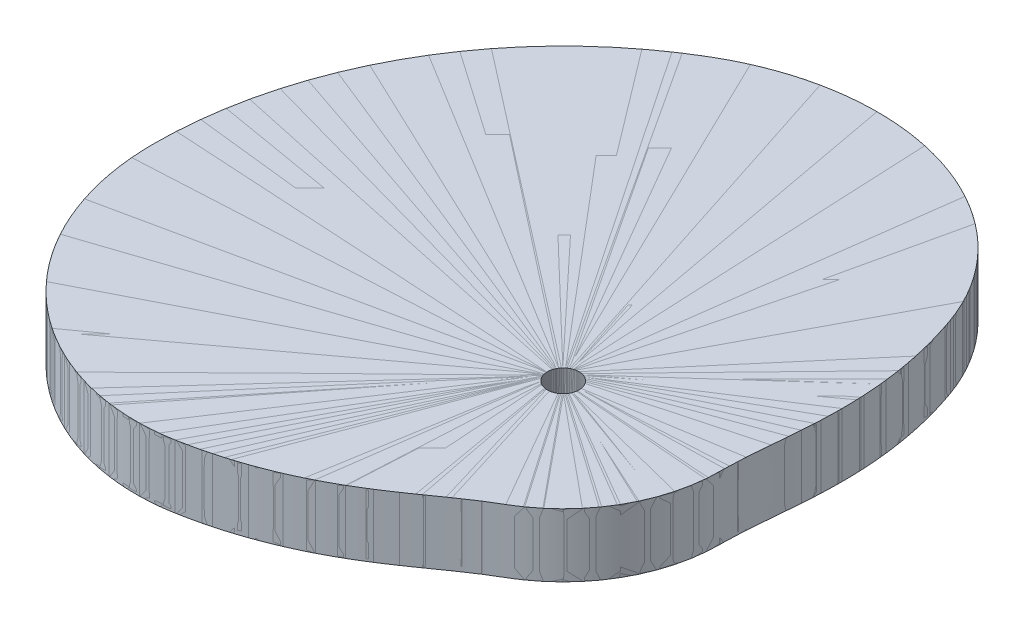
SolidWorks part; units mm, degrees
ref_plane "前视基准面" through (0, 0, 0) normal (0, 0, 1) x (1, 0, 0)
ref_plane "上视基准面" through (0, 0, 0) normal (0, 1, 0) x (1, 0, 0)
ref_plane "右视基准面" through (0, 0, 0) normal (1, 0, 0) x (0, 0, -1)
other "Configuration Table"
sketch "草图1" plane through (0, 0, 0) normal (0, 0, 1) x (1, 0, 0)
  line L0 (0, -20200) -> (0, 200) construction
  line L1 (5, 0) -> (130, 0)
  line L2 (130, 0) -> (130, -20)
  line L3 (130, -20) -> (5, -20)
  line L4 (5, -20) -> (5, 0)
revolve "旋转1" add sketch "草图1" angle 360 about L0
sketch "草图2" plane through (0, 0, 0) normal (0, 1, 0) x (1, 0, 0)
  line L0 (0, 0) -> (50, 0) construction
  arc A0 (49.5, 0) -> (49.5868, 4.4012) centre (162.6884, -0.0309) cw
  arc A1 (49.5868, 4.4012) -> (49.8358, 8.9099) centre (194.8962, -1.3625) cw
  arc A2 (49.8358, 8.9099) -> (50.213, 13.6312) centre (319.2819, -10.2396) cw
  arc A3 (50.213, 13.6312) -> (50.663, 18.6649) centre (3915.5987, -329.3799) cw
  arc A4 (50.663, 18.6649) -> (51.1105, 24.1021) centre (-309.0879, 51.0135) ccw
  arc A5 (51.1105, 24.1021) -> (51.462, 30.0213) centre (-145.0959, 38.7218) ccw
  arc A6 (51.462, 30.0213) -> (51.6071, 36.4857) centre (-98.2755, 36.6179) ccw
  arc A7 (51.6071, 36.4857) -> (51.4215, 43.5396) centre (-79.0428, 36.5763) ccw
  arc A8 (51.4215, 43.5396) -> (50.7686, 51.2069) centre (-70.6967, 37.0025) ccw
  arc A9 (50.7686, 51.2069) -> (49.5032, 59.4882) centre (-67.8394, 37.3214) ccw
  arc A10 (49.5032, 59.4882) -> (47.4745, 68.3602) centre (-68.1876, 37.2436) ccw
  arc A11 (47.4745, 68.3602) -> (44.5307, 77.769) centre (-70.5306, 36.6049) ccw
  arc A12 (44.5307, 77.769) -> (40.298, 87.1155) centre (-14.8762, 56.4971) ccw
  arc A13 (40.298, 87.1155) -> (34.5682, 95.7489) centre (-16.8999, 55.3723) ccw
  arc A14 (34.5682, 95.7489) -> (27.4814, 103.4715) centre (-18.8355, 53.855) ccw
  arc A15 (27.4814, 103.4715) -> (19.2044, 110.1045) centre (-20.5276, 52.0448) ccw
  arc A16 (19.2044, 110.1045) -> (9.925, 115.4961) centre (-21.8914, 50.0559) ccw
  arc A17 (9.925, 115.4961) -> (-0.1518, 119.5233) centre (-22.8862, 48.016) ccw
  arc A18 (-0.1518, 119.5233) -> (-10.8076, 122.0939) centre (-23.5139, 46.0515) ccw
  arc A19 (-10.8076, 122.0939) -> (-21.8153, 123.1479) centre (-23.8137, 44.2768) ccw
  arc A20 (-21.8153, 123.1479) -> (-32.943, 122.6584) centre (-23.8548, 42.7851) ccw
  arc A21 (-32.943, 122.6584) -> (-43.9585, 120.6313) centre (-23.7281, 41.6427) ccw
  arc A22 (-43.9585, 120.6313) -> (-54.634, 117.105) centre (-23.5377, 40.8858) ccw
  arc A23 (-54.634, 117.105) -> (-64.75, 112.1503) centre (-23.3663, 40.4621) ccw
  arc A24 (-64.75, 112.1503) -> (-129.5, 0) centre (0, 0) ccw
  arc A25 (-129.5, 0) -> (-128.7329, -11.2381) centre (-46.7244, 0.0047) ccw
  arc A26 (-128.7329, -11.2381) -> (-126.449, -22.2464) centre (-47.177, -0.0586) ccw
  arc A27 (-126.449, -22.2464) -> (-122.6968, -32.7998) centre (-47.9277, -0.2722) ccw
  arc A28 (-122.6968, -32.7998) -> (-117.5569, -42.6814) centre (-48.9804, -0.7337) ccw
  arc A29 (-117.5569, -42.6814) -> (-111.1402, -51.6872) centre (-50.2517, -1.5152) ccw
  arc A30 (-111.1402, -51.6872) -> (-103.5861, -59.6302) centre (-51.6388, -2.6621) ccw
  arc A31 (-103.5861, -59.6302) -> (-95.0601, -66.3433) centre (-53.0262, -4.1879) ccw
  arc A32 (-95.0601, -66.3433) -> (-85.7511, -71.6838) centre (-54.2954, -6.0694) ccw
  arc A33 (-85.7511, -71.6838) -> (-75.8682, -75.5353) centre (-55.3359, -8.2449) ccw
  arc A34 (-75.8682, -75.5353) -> (-65.6369, -77.8113) centre (-56.0575, -10.6155) ccw
  arc A35 (-65.6369, -77.8113) -> (-55.2952, -78.4568) centre (-56.4038, -13.0504) ccw
  arc A36 (-55.2952, -78.4568) -> (-45.0846, -77.4492) centre (-56.366, -15.3653) ccw
  arc A37 (-45.0846, -77.4492) -> (-35.4644, -75.2942) centre (-66.9661, 42.7788) ccw
  arc A38 (-35.4644, -75.2942) -> (-26.7667, -72.6152) centre (-66.3477, 40.4304) ccw
  arc A39 (-26.7667, -72.6152) -> (-18.9621, -69.5703) centre (-66.241, 40.09) ccw
  arc A40 (-18.9621, -69.5703) -> (-11.9957, -66.3021) centre (-67.3934, 42.7239) ccw
  arc A41 (-11.9957, -66.3021) -> (-5.794, -62.9359) centre (-71.1974, 50.1649) ccw
  arc A42 (-5.794, -62.9359) -> (-0.2683, -59.578) centre (-80.8498, 66.8001) ccw
  arc A43 (-0.2683, -59.578) -> (4.6822, -56.314) centre (-106.082, 106.2959) ccw
  arc A44 (4.6822, -56.314) -> (9.1672, -53.2079) centre (-198.7229, 242.1712) ccw
  arc A45 (9.1672, -53.2079) -> (13.3016, -50.3013) centre (2243.0507, -3226.318) cw
  arc A46 (13.3016, -50.3013) -> (17.2017, -47.614) centre (168.5087, -271.3864) cw
  arc A47 (17.2017, -47.614) -> (20.9819, -45.144) centre (98.6281, -168.1038) cw
  arc A48 (20.9819, -45.144) -> (24.75, -42.8683) centre (81.371, -140.8768) cw
  arc A49 (24.75, -42.8683) -> (49.5, 0) centre (0, 0) ccw
extrude "切除-拉伸1" cut sketch "草图2" along normal blind 10 and the other way blind 30 flip side to cut
sketch "草图3" plane through (0, 0, 0) normal (0, 1, 0) x (1, 0, 0)
  circle A0 centre (0, 0) radius 5 construction
  circle A1 centre (0, 0) radius 5
  arc A50 (24.75, -42.8683) -> (20.9819, -45.144) centre (81.371, -140.8768) ccw
  arc A51 (24.75, -42.8683) -> (49.5, 0) centre (0, 0) ccw
  arc A52 (49.5868, 4.4012) -> (49.5, 0) centre (162.6884, -0.0309) ccw
  arc A53 (49.8358, 8.9099) -> (49.5868, 4.4012) centre (194.8962, -1.3625) ccw
  arc A54 (50.213, 13.6312) -> (49.8358, 8.9099) centre (319.2819, -10.2396) ccw
  arc A55 (50.663, 18.6649) -> (50.213, 13.6312) centre (3915.5987, -329.3799) ccw
  arc A56 (50.663, 18.6649) -> (51.1105, 24.1021) centre (-309.0879, 51.0135) ccw
  arc A57 (51.1105, 24.1021) -> (51.462, 30.0213) centre (-145.0959, 38.7218) ccw
  arc A58 (51.462, 30.0213) -> (51.6071, 36.4857) centre (-98.2755, 36.6179) ccw
  arc A59 (51.6071, 36.4857) -> (51.4215, 43.5396) centre (-79.0428, 36.5763) ccw
  arc A60 (51.4215, 43.5396) -> (50.7686, 51.2069) centre (-70.6967, 37.0025) ccw
  arc A61 (50.7686, 51.2069) -> (49.5032, 59.4882) centre (-67.8394, 37.3214) ccw
  arc A62 (49.5032, 59.4882) -> (47.4745, 68.3602) centre (-68.1876, 37.2436) ccw
  arc A63 (47.4745, 68.3602) -> (44.5307, 77.769) centre (-70.5306, 36.6049) ccw
  arc A64 (44.5307, 77.769) -> (40.298, 87.1155) centre (-14.8762, 56.4971) ccw
  arc A65 (40.298, 87.1155) -> (34.5682, 95.7489) centre (-16.8999, 55.3723) ccw
  arc A66 (34.5682, 95.7489) -> (27.4814, 103.4715) centre (-18.8355, 53.855) ccw
  arc A67 (27.4814, 103.4715) -> (19.2044, 110.1045) centre (-20.5276, 52.0448) ccw
  arc A68 (19.2044, 110.1045) -> (9.925, 115.4961) centre (-21.8914, 50.0559) ccw
  arc A69 (9.925, 115.4961) -> (-0.1518, 119.5233) centre (-22.8862, 48.016) ccw
  arc A70 (-0.1518, 119.5233) -> (-10.8076, 122.0939) centre (-23.5139, 46.0515) ccw
  arc A71 (-10.8076, 122.0939) -> (-21.8153, 123.1479) centre (-23.8137, 44.2768) ccw
  arc A72 (-21.8153, 123.1479) -> (-32.943, 122.6584) centre (-23.8548, 42.7851) ccw
  arc A73 (-32.943, 122.6584) -> (-43.9585, 120.6313) centre (-23.7281, 41.6427) ccw
  arc A74 (-43.9585, 120.6313) -> (-54.634, 117.105) centre (-23.5377, 40.8858) ccw
  arc A75 (-54.634, 117.105) -> (-64.75, 112.1503) centre (-23.3663, 40.4621) ccw
  arc A76 (-64.75, 112.1503) -> (-129.5, 0) centre (0, 0) ccw
  arc A77 (-129.5, 0) -> (-128.7329, -11.2381) centre (-46.7244, 0.0047) ccw
  arc A78 (-128.7329, -11.2381) -> (-126.449, -22.2464) centre (-47.177, -0.0586) ccw
  arc A79 (-126.449, -22.2464) -> (-122.6968, -32.7998) centre (-47.9277, -0.2722) ccw
  arc A80 (-122.6968, -32.7998) -> (-117.5569, -42.6814) centre (-48.9804, -0.7337) ccw
  arc A81 (-117.5569, -42.6814) -> (-111.1402, -51.6872) centre (-50.2517, -1.5152) ccw
  arc A82 (-111.1402, -51.6872) -> (-103.5861, -59.6302) centre (-51.6388, -2.6621) ccw
  arc A83 (-103.5861, -59.6302) -> (-95.0601, -66.3433) centre (-53.0262, -4.1879) ccw
  arc A84 (-95.0601, -66.3433) -> (-85.7511, -71.6838) centre (-54.2954, -6.0694) ccw
  arc A85 (-85.7511, -71.6838) -> (-75.8682, -75.5353) centre (-55.3359, -8.2449) ccw
  arc A86 (-75.8682, -75.5353) -> (-65.6369, -77.8113) centre (-56.0575, -10.6155) ccw
  arc A87 (-65.6369, -77.8113) -> (-55.2952, -78.4568) centre (-56.4038, -13.0504) ccw
  arc A88 (-55.2952, -78.4568) -> (-45.0846, -77.4492) centre (-56.366, -15.3653) ccw
  arc A89 (-45.0846, -77.4492) -> (-35.4644, -75.2942) centre (-66.9661, 42.7788) ccw
  arc A90 (-35.4644, -75.2942) -> (-26.7667, -72.6152) centre (-66.3477, 40.4304) ccw
  arc A91 (-26.7667, -72.6152) -> (-18.9621, -69.5703) centre (-66.241, 40.09) ccw
  arc A92 (-18.9621, -69.5703) -> (-11.9957, -66.3021) centre (-67.3934, 42.7239) ccw
  arc A93 (-11.9957, -66.3021) -> (-5.794, -62.9359) centre (-71.1974, 50.1649) ccw
  arc A94 (-5.794, -62.9359) -> (-0.2683, -59.578) centre (-80.8498, 66.8001) ccw
  arc A95 (-0.2683, -59.578) -> (4.6822, -56.314) centre (-106.082, 106.2959) ccw
  arc A96 (4.6822, -56.314) -> (9.1672, -53.2079) centre (-198.7229, 242.1712) ccw
  arc A97 (13.3016, -50.3013) -> (9.1672, -53.2079) centre (2243.0507, -3226.318) ccw
  arc A98 (17.2017, -47.614) -> (13.3016, -50.3013) centre (168.5087, -271.3864) ccw
  arc A99 (20.9819, -45.144) -> (17.2017, -47.614) centre (98.6281, -168.1038) ccw
  arc A100 (24.75, -42.8683) -> (20.9819, -45.144) centre (81.371, -140.8768) ccw construction
  arc A101 (24.75, -42.8683) -> (49.5, 0) centre (0, 0) ccw construction
  arc A102 (49.5868, 4.4012) -> (49.5, 0) centre (162.6884, -0.0309) ccw construction
  arc A103 (49.8358, 8.9099) -> (49.5868, 4.4012) centre (194.8962, -1.3625) ccw construction
  arc A104 (50.213, 13.6312) -> (49.8358, 8.9099) centre (319.2819, -10.2396) ccw construction
  arc A105 (50.663, 18.6649) -> (50.213, 13.6312) centre (3915.5987, -329.3799) ccw construction
  arc A106 (50.663, 18.6649) -> (51.1105, 24.1021) centre (-309.0879, 51.0135) ccw construction
  arc A107 (51.1105, 24.1021) -> (51.462, 30.0213) centre (-145.0959, 38.7218) ccw construction
  arc A108 (51.462, 30.0213) -> (51.6071, 36.4857) centre (-98.2755, 36.6179) ccw construction
  arc A109 (51.6071, 36.4857) -> (51.4215, 43.5396) centre (-79.0428, 36.5763) ccw construction
  arc A110 (51.4215, 43.5396) -> (50.7686, 51.2069) centre (-70.6967, 37.0025) ccw construction
  arc A111 (50.7686, 51.2069) -> (49.5032, 59.4882) centre (-67.8394, 37.3214) ccw construction
  arc A112 (49.5032, 59.4882) -> (47.4745, 68.3602) centre (-68.1876, 37.2436) ccw construction
  arc A113 (47.4745, 68.3602) -> (44.5307, 77.769) centre (-70.5306, 36.6049) ccw construction
  arc A114 (44.5307, 77.769) -> (40.298, 87.1155) centre (-14.8762, 56.4971) ccw construction
  arc A115 (40.298, 87.1155) -> (34.5682, 95.7489) centre (-16.8999, 55.3723) ccw construction
  arc A116 (34.5682, 95.7489) -> (27.4814, 103.4715) centre (-18.8355, 53.855) ccw construction
  arc A117 (27.4814, 103.4715) -> (19.2044, 110.1045) centre (-20.5276, 52.0448) ccw construction
  arc A118 (19.2044, 110.1045) -> (9.925, 115.4961) centre (-21.8914, 50.0559) ccw construction
  arc A119 (9.925, 115.4961) -> (-0.1518, 119.5233) centre (-22.8862, 48.016) ccw construction
  arc A120 (-0.1518, 119.5233) -> (-10.8076, 122.0939) centre (-23.5139, 46.0515) ccw construction
  arc A121 (-10.8076, 122.0939) -> (-21.8153, 123.1479) centre (-23.8137, 44.2768) ccw construction
  arc A122 (-21.8153, 123.1479) -> (-32.943, 122.6584) centre (-23.8548, 42.7851) ccw construction
  arc A123 (-32.943, 122.6584) -> (-43.9585, 120.6313) centre (-23.7281, 41.6427) ccw construction
  arc A124 (-43.9585, 120.6313) -> (-54.634, 117.105) centre (-23.5377, 40.8858) ccw construction
  arc A125 (-54.634, 117.105) -> (-64.75, 112.1503) centre (-23.3663, 40.4621) ccw construction
  arc A126 (-64.75, 112.1503) -> (-129.5, 0) centre (0, 0) ccw construction
  arc A127 (-129.5, 0) -> (-128.7329, -11.2381) centre (-46.7244, 0.0047) ccw construction
  arc A128 (-128.7329, -11.2381) -> (-126.449, -22.2464) centre (-47.177, -0.0586) ccw construction
  arc A129 (-126.449, -22.2464) -> (-122.6968, -32.7998) centre (-47.9277, -0.2722) ccw construction
  arc A130 (-122.6968, -32.7998) -> (-117.5569, -42.6814) centre (-48.9804, -0.7337) ccw construction
  arc A131 (-117.5569, -42.6814) -> (-111.1402, -51.6872) centre (-50.2517, -1.5152) ccw construction
  arc A132 (-111.1402, -51.6872) -> (-103.5861, -59.6302) centre (-51.6388, -2.6621) ccw construction
  arc A133 (-103.5861, -59.6302) -> (-95.0601, -66.3433) centre (-53.0262, -4.1879) ccw construction
  arc A134 (-95.0601, -66.3433) -> (-85.7511, -71.6838) centre (-54.2954, -6.0694) ccw construction
  arc A135 (-85.7511, -71.6838) -> (-75.8682, -75.5353) centre (-55.3359, -8.2449) ccw construction
  arc A136 (-75.8682, -75.5353) -> (-65.6369, -77.8113) centre (-56.0575, -10.6155) ccw construction
  arc A137 (-65.6369, -77.8113) -> (-55.2952, -78.4568) centre (-56.4038, -13.0504) ccw construction
  arc A138 (-55.2952, -78.4568) -> (-45.0846, -77.4492) centre (-56.366, -15.3653) ccw construction
  arc A139 (-45.0846, -77.4492) -> (-35.4644, -75.2942) centre (-66.9661, 42.7788) ccw construction
  arc A140 (-35.4644, -75.2942) -> (-26.7667, -72.6152) centre (-66.3477, 40.4304) ccw construction
  arc A141 (-26.7667, -72.6152) -> (-18.9621, -69.5703) centre (-66.241, 40.09) ccw construction
  arc A142 (-18.9621, -69.5703) -> (-11.9957, -66.3021) centre (-67.3934, 42.7239) ccw construction
  arc A143 (-11.9957, -66.3021) -> (-5.794, -62.9359) centre (-71.1974, 50.1649) ccw construction
  arc A144 (-5.794, -62.9359) -> (-0.2683, -59.578) centre (-80.8498, 66.8001) ccw construction
  arc A145 (-0.2683, -59.578) -> (4.6822, -56.314) centre (-106.082, 106.2959) ccw construction
  arc A146 (4.6822, -56.314) -> (9.1672, -53.2079) centre (-198.7229, 242.1712) ccw construction
  arc A147 (13.3016, -50.3013) -> (9.1672, -53.2079) centre (2243.0507, -3226.318) ccw construction
  arc A148 (17.2017, -47.614) -> (13.3016, -50.3013) centre (168.5087, -271.3864) ccw construction
  arc A149 (20.9819, -45.144) -> (17.2017, -47.614) centre (98.6281, -168.1038) ccw construction
  spline S0 degree 3 poles (20.0297, -45.7505) (19.3964, -46.1573) (18.7664, -46.569) (18.1396, -46.9855) (18.0351, -47.0549) (17.8263, -47.1941) (17.5136, -47.4034) (17.3056, -47.5437) (17.2017, -47.614) (17.0927, -47.6877) (16.8749, -47.8352) (16.5484, -48.057) (16.3309, -48.2052) (16.2223, -48.2794) (15.5703, -48.7244) (14.9202, -49.1723) (14.2722, -49.6231) (14.1642, -49.6982) (13.9482, -49.8486) (13.6246, -50.0745) (13.4092, -50.2257) (13.3016, -50.3013) (13.1867, -50.382) (12.9569, -50.5433) (12.6122, -50.7853) (12.3825, -50.9467) (12.2676, -51.0274) (11.5784, -51.5116) (10.8893, -51.9961) (10.2004, -52.4807) (9.9617, -52.6487) (9.4842, -52.9847) (8.768, -53.4888) (8.2897, -53.8236) (8.0504, -53.9908) (7.3048, -54.5113) (6.5573, -55.029) (5.8079, -55.5439) (5.683, -55.6297) (5.433, -55.8011) (5.0578, -56.0579) (4.8075, -56.2287) (4.6822, -56.314) (4.5461, -56.4068) (4.2738, -56.5921) (3.8641, -56.8686) (3.5907, -57.0523) (3.4539, -57.144) (2.6329, -57.6942) (1.8077, -58.2383) (0.9785, -58.776) (0.8403, -58.8657) (0.5637, -59.0446) (0.1481, -59.3119) (-0.1294, -59.4894) (-0.2683, -59.578) (-0.4197, -59.6746) (-0.7228, -59.8674) (-1.1789, -60.1545) (-1.4835, -60.3449) (-1.636, -60.4398) (-2.551, -61.0094) (-3.472, -61.5691) (-4.399, -62.1189) (-4.5535, -62.2105) (-4.8629, -62.3932) (-5.3278, -62.6655) (-5.6385, -62.846) (-5.794, -62.9359) (-5.9636, -63.0341) (-6.3034, -63.2298) (-6.8146, -63.5205) (-7.1562, -63.713) (-7.3272, -63.8088) (-8.3533, -64.3838) (-9.3871, -64.9449) (-10.4283, -65.4921) (-10.6019, -65.5832) (-10.9494, -65.7648) (-11.4718, -66.0348) (-11.8209, -66.2133) (-11.9957, -66.3021) (-12.1863, -66.399) (-12.5679, -66.5918) (-13.142, -66.8777) (-13.5257, -67.0663) (-13.7178, -67.1602) (-14.8704, -67.7232) (-16.0317, -68.268) (-17.2015, -68.7945) (-17.3964, -68.8822) (-17.7868, -69.0567) (-18.3737, -69.3153) (-18.7658, -69.4857) (-18.9621, -69.5703) (-19.1759, -69.6625) (-19.6038, -69.8456) (-20.2475, -70.1163) (-20.6776, -70.2944) (-20.8929, -70.3828) (-22.1849, -70.9131) (-23.486, -71.4207) (-24.7958, -71.9054) (-25.0141, -71.9862) (-25.4511, -72.1465) (-26.1081, -72.3831) (-26.547, -72.5382) (-26.7667, -72.6152) (-27.0053, -72.6987) (-27.4832, -72.8643) (-28.2015, -73.1082) (-28.6814, -73.2678) (-28.9216, -73.3468) (-30.3629, -73.8209) (-31.813, -74.2675) (-33.2713, -74.6865) (-33.5143, -74.7564) (-34.0008, -74.8945) (-34.7319, -75.0971) (-35.2201, -75.229) (-35.4644, -75.2942) (-35.7291, -75.3648) (-36.2589, -75.5042) (-37.055, -75.7081) (-37.5866, -75.8404) (-37.8527, -75.9056) (-39.449, -76.2972) (-41.0529, -76.6565) (-42.6637, -76.9834) (-42.9322, -77.0379) (-43.4694, -77.145) (-44.2764, -77.3003) (-44.8151, -77.4002) (-45.0846, -77.4492) (-45.3653, -77.5003) (-45.927, -77.6005) (-46.7726, -77.7344) (-47.3372, -77.8173) (-47.6197, -77.8568) (-49.3156, -78.0942) (-51.0197, -78.2623) (-52.7293, -78.361) (-53.0141, -78.3775) (-53.584, -78.4065) (-54.4395, -78.4386) (-55.0099, -78.452) (-55.2952, -78.4568) (-55.5833, -78.4617) (-56.1595, -78.4677) (-57.024, -78.4652) (-57.6001, -78.4559) (-57.8882, -78.4494) (-59.617, -78.4101) (-61.3428, -78.3024) (-63.0631, -78.1264) (-63.3444, -78.0976) (-63.9068, -78.0364) (-64.7492, -77.9337) (-65.3098, -77.8578) (-65.5898, -77.818) (-65.8836, -77.7764) (-66.4705, -77.6892) (-67.3494, -77.5468) (-67.9339, -77.4443) (-68.2258, -77.3911) (-69.9465, -77.0775) (-71.6539, -76.6977) (-73.3453, -76.2522) (-73.6171, -76.1806) (-74.16, -76.034) (-74.9716, -75.8041) (-75.5106, -75.644) (-75.7796, -75.5623) (-76.0716, -75.4736) (-76.6545, -75.2924) (-77.5254, -75.0093) (-78.1034, -74.813) (-78.3917, -74.713) (-80.0639, -74.133) (-81.713, -73.4903) (-83.3367, -72.7858) (-83.5937, -72.6744) (-84.1063, -72.4483) (-84.8713, -72.1002) (-85.3783, -71.8618) (-85.6311, -71.7412) (-85.9137, -71.6063) (-86.4772, -71.333) (-87.3173, -70.912) (-87.8735, -70.6241) (-88.1507, -70.4784) (-89.7358, -69.6453) (-91.2891, -68.7542) (-92.8084, -67.8064) (-93.0452, -67.6587) (-93.5172, -67.3605) (-94.2201, -66.9051) (-94.685, -66.596) (-94.9166, -66.4401) (-95.1829, -66.261) (-95.7131, -65.8992) (-96.5014, -65.3464) (-97.0222, -64.9712) (-97.2813, -64.7819) (-98.7435, -63.714) (-100.166, -62.5939) (-101.5471, -61.4231) (-101.7588, -61.2436) (-102.1803, -60.8823) (-102.8066, -60.3333) (-103.2199, -59.9626) (-103.4255, -59.7762) (-103.6691, -59.5553) (-104.1535, -59.1104) (-104.8716, -58.4337) (-105.3445, -57.9766) (-105.5794, -57.7465) (-106.8861, -56.467) (-108.1464, -55.1417) (-109.3589, -53.7725) (-109.5409, -53.5669) (-109.9028, -53.1538) (-110.4392, -52.5283) (-110.7921, -52.1075) (-110.9674, -51.8962) (-111.183, -51.6364) (-111.6107, -51.1142) (-112.2423, -50.3225) (-112.6565, -49.7894) (-112.8619, -49.5216) (-113.9844, -48.0575) (-115.055, -46.555) (-116.0722, -45.0159) (-116.2205, -44.7915) (-116.5147, -44.3412) (-116.9493, -43.6614) (-117.2343, -43.2052) (-117.3756, -42.9764) (-117.5585, -42.6802) (-117.9205, -42.0855) (-118.4519, -41.1863) (-118.7984, -40.5824) (-118.9696, -40.2793) (-119.8837, -38.6614) (-120.7413, -37.0128) (-121.5411, -35.3355) (-121.6521, -35.1028) (-121.8717, -34.6364) (-122.1946, -33.9336) (-122.4052, -33.463) (-122.5094, -33.2272) (-122.6562, -32.895) (-122.9454, -32.2286) (-123.3658, -31.2231) (-123.637, -30.5492) (-123.7704, -30.2114) (-124.4565, -28.4733) (-125.0825, -26.7127) (-125.6476, -24.9316) (-125.7181, -24.7093) (-125.8573, -24.2641) (-126.0603, -23.5945) (-126.1918, -23.147) (-126.2565, -22.9229) (-126.3651, -22.5476) (-126.5767, -21.7955) (-126.8782, -20.6626) (-127.0684, -19.9048) (-127.1608, -19.5252) (-127.6043, -17.7028) (-127.9853, -15.8663) (-128.3034, -14.0178) (-128.3479, -13.759) (-128.4345, -13.241) (-128.557, -12.4627) (-128.6336, -11.9432) (-128.6707, -11.6832) (-128.7219, -11.3238) (-128.8197, -10.6043) (-128.9522, -9.523) (-129.0311, -8.8011) (-129.0681, -8.44) (-129.2598, -6.5706) (-129.3878, -4.6958) (-129.4519, -2.8177) (-129.4625, -2.5047) (-129.4803, -1.8787) (-129.4977, -0.9394) (-129.5, -0.3131) (-129.5, 0) (-129.5, 0.314) (-129.4977, 0.942) (-129.4874, 1.8841) (-129.476, 2.512) (-129.4692, 2.8259) (-128.4819, 48.0581) (-105.8604, 87.2395) (-67.1819, 110.7106) (-66.9135, 110.8735) (-66.3754, 111.1974) (-65.5647, 111.6773) (-65.0219, 111.9933) (-64.75, 112.1503) (-64.4788, 112.3069) (-63.9354, 112.618) (-63.1131, 113.0726) (-62.5621, 113.3702) (-62.2858, 113.5174) (-60.6272, 114.401) (-58.9396, 115.2276) (-57.2248, 115.9962) (-56.8935, 116.1448) (-56.229, 116.4374) (-55.2263, 116.8633) (-54.5543, 117.1384) (-54.2174, 117.2737) (-53.9737, 117.3716) (-53.4854, 117.565) (-52.7502, 117.8481) (-52.2583, 118.0321) (-52.0119, 118.1229) (-50.2521, 118.7717) (-48.4711, 119.36) (-46.6711, 119.8871) (-46.2961, 119.9968) (-45.5447, 120.2111) (-44.4129, 120.5164) (-43.6557, 120.7092) (-43.2764, 120.8028) (-43.05, 120.8588) (-42.5967, 120.9687) (-41.9153, 121.1276) (-41.4602, 121.2297) (-41.2324, 121.2798) (-39.4074, 121.6809) (-37.5696, 122.0191) (-35.7214, 122.294) (-35.3621, 122.3474) (-34.6429, 122.4494) (-33.5619, 122.5881) (-32.8402, 122.6709) (-32.4791, 122.7099) (-32.2228, 122.7375) (-31.71, 122.7904) (-30.9399, 122.8622) (-30.4261, 122.9052) (-30.1691, 122.9254) (-28.3166, 123.0714) (-26.4601, 123.1531) (-24.6019, 123.1703) (-24.2538, 123.1736) (-23.5576, 123.1755) (-22.5132, 123.1649) (-21.8171, 123.1487) (-21.4692, 123.1384) (-21.2004, 123.1304) (-20.6628, 123.1118) (-19.8567, 123.0753) (-19.3197, 123.0456) (-19.0512, 123.0294) (-17.2097, 122.918) (-15.3732, 122.7422) (-13.544, 122.502) (-13.2093, 122.4581) (-12.5406, 122.3659) (-11.5392, 122.2148) (-10.873, 122.1055) (-10.5403, 122.0487) (-10.2696, 122.0025) (-9.7287, 121.9073) (-8.9189, 121.7555) (-8.3801, 121.6487) (-8.1111, 121.5938) (-6.3191, 121.2284) (-4.5412, 120.7995) (-2.7798, 120.3077) (-2.463, 120.2193) (-1.8307, 120.0383) (-0.8857, 119.7548) (-0.2582, 119.5577) (0.0549, 119.4572) (0.3192, 119.3724) (0.8469, 119.1998) (1.6354, 118.9319) (2.1591, 118.7475) (2.4204, 118.6539) (4.1249, 118.0433) (5.8062, 117.3714) (7.4621, 116.639) (7.7556, 116.5092) (8.3409, 116.2459) (9.2139, 115.8396) (9.7922, 115.5613) (10.0805, 115.4203) (10.3313, 115.2976) (10.8314, 115.0495) (11.5773, 114.6685) (12.0715, 114.4089) (12.3179, 114.2776) (13.8984, 113.4357) (15.4467, 112.5361) (16.9608, 111.58) (17.2255, 111.4128) (17.7529, 111.075) (18.5376, 110.5579) (19.0561, 110.2066) (19.3142, 110.0293) (19.545, 109.8707) (20.0049, 109.5507) (20.6889, 109.0623) (21.141, 108.7314) (21.366, 108.5646) (22.7879, 107.5107) (24.1691, 106.4038) (25.5075, 105.2457) (25.7383, 105.046) (26.1972, 104.6436) (26.8779, 104.031) (27.3263, 103.6168) (27.5491, 103.4082) (27.7543, 103.2161) (28.1625, 102.8294) (28.7674, 102.2414) (29.1658, 101.8446) (29.3637, 101.645) (30.5952, 100.4029) (31.7778, 99.1142) (32.9098, 97.7808) (33.1018, 97.5546) (33.4828, 97.0997) (34.0455, 96.4098) (34.4145, 95.945) (34.5975, 95.7115) (34.7719, 95.4888) (35.118, 95.0413) (35.6281, 94.3631) (35.9623, 93.9067) (36.1279, 93.6774) (37.1405, 92.2757) (38.0967, 90.8349) (38.9951, 89.3573) (39.1447, 89.1111) (39.4409, 88.6168) (39.8753, 87.8694) (40.1582, 87.3674) (40.298, 87.1155) (40.4365, 86.866) (40.7101, 86.3653) (41.11, 85.6083) (41.3698, 85.1003) (41.498, 84.8454) (42.2673, 83.3155) (42.9737, 81.7556) (43.6161, 80.1683) (43.7232, 79.9038) (43.9336, 79.3735) (44.2405, 78.5742) (44.4346, 78.0376) (44.5307, 77.769) (44.623, 77.5111) (44.8058, 76.9946) (45.0748, 76.2181) (45.2507, 75.6993) (45.3377, 75.4395) (45.86, 73.8811) (46.3508, 72.3124) (46.8099, 70.7342) (46.8864, 70.4712) (47.0376, 69.9446) (47.2592, 69.1532) (47.4033, 68.6247) (47.4745, 68.3602) (47.5402, 68.116) (47.6701, 67.6272) (47.8601, 66.8928) (47.9837, 66.4024) (48.0448, 66.157) (48.4111, 64.6846) (48.7493, 63.2055) (49.0594, 61.7203) (49.111, 61.4727) (49.2128, 60.9774) (49.3608, 60.2333) (49.4563, 59.7367) (49.5032, 59.4882) (49.5465, 59.2595) (49.6316, 58.8018) (49.7551, 58.1146) (49.8348, 57.6559) (49.874, 57.4265) (50.1091, 56.0498) (50.3201, 54.6693) (50.5068, 53.2852) (50.5379, 53.0545) (50.5988, 52.593) (50.6862, 51.9002) (50.7416, 51.438) (50.7686, 51.2069) (50.7934, 50.9945) (50.842, 50.5697) (50.9115, 49.9321) (50.9555, 49.5068) (50.977, 49.2941) (51.106, 48.0179) (51.2148, 46.7397) (51.3035, 45.46) (51.3183, 45.2468) (51.3467, 44.8202) (51.3862, 44.18) (51.4101, 43.7531) (51.4215, 43.5396) (51.4319, 43.3439) (51.4519, 42.9523) (51.4793, 42.3648) (51.4958, 41.9731) (51.5036, 41.7772) (51.5504, 40.6019) (51.5814, 39.4261) (51.5964, 38.2499) (51.599, 38.0539) (51.6031, 37.6619) (51.6069, 37.0738) (51.6073, 36.6817) (51.6071, 36.4857) (51.607, 36.3061) (51.606, 35.9468) (51.6026, 35.4079) (51.5991, 35.0487) (51.597, 34.8691) (51.5844, 33.7914) (51.5602, 32.7139) (51.5244, 31.6367) (51.5184, 31.4572) (51.5058, 31.0982) (51.4853, 30.5597) (51.4699, 30.2008) (51.462, 30.0213) (51.4547, 29.8568) (51.4397, 29.5277) (51.416, 29.0341) (51.3993, 28.7051) (51.3908, 28.5406) (51.3397, 27.5536) (51.2811, 26.567) (51.2151, 25.5809) (51.2041, 25.4165) (51.1817, 25.0878) (51.1471, 24.5949) (51.1228, 24.2663) (51.1105, 24.1021) (51.0992, 23.951) (51.0764, 23.6487) (51.0417, 23.1954) (51.0182, 22.8932) (51.0063, 22.7422) (50.9352, 21.8357) (50.8606, 20.9295) (50.7825, 20.0236) (50.7575, 19.7327) (50.7067, 19.1511) (50.6282, 18.2788) (50.5759, 17.6973) (50.5499, 17.4065) (50.4746, 16.5676) (50.3996, 15.7286) (50.3249, 14.8897) (50.3124, 14.7498) (50.2875, 14.4702) (50.2502, 14.0507) (50.2254, 13.771) (50.213, 13.6312) (50.2013, 13.5001) (50.1781, 13.238) (50.1443, 12.8448) (50.122, 12.5826) (50.1109, 12.4515) (50.0446, 11.6649) (49.9817, 10.878) (49.9223, 10.0908) (49.9124, 9.9596) (49.8928, 9.6972) (49.864, 9.3036) (49.8451, 9.0411) (49.8358, 8.9099) (49.8269, 8.7847) (49.8093, 8.5345) (49.7844, 8.159) (49.7683, 7.9086) (49.7604, 7.7834) (49.7131, 7.0323) (49.6716, 6.2808) (49.6359, 5.529) (49.63, 5.4037) (49.6184, 5.1531) (49.602, 4.7772) (49.5918, 4.5265) (49.5868, 4.4012) (49.582, 4.279) (49.5726, 4.0346) (49.5603, 3.6679) (49.5527, 3.4235) (49.5491, 3.3013) (49.5275, 2.5678) (49.513, 1.8343) (49.5057, 1.1006) (49.5032, 0.8557) (49.4999, 0.3658) (49.5004, -0.369) (49.4932, -0.8588) (49.4877, -1.1036) (49.1025, -18.3752) (40.4646, -33.3365) (25.6996, -42.3058) (25.4903, -42.4329) (25.0698, -42.6842) (24.4331, -43.0511) (24.0106, -43.2989) (23.7997, -43.4234) (23.168, -43.7966) (22.5399, -44.176) (21.9156, -44.5614) (21.8115, -44.6256) (21.6036, -44.7544) (21.2922, -44.9484) (21.0853, -45.0787) (20.9819, -45.144) (20.8758, -45.211) (20.6639, -45.3452) (20.3465, -45.5474) (20.1352, -45.6827) (20.0297, -45.7505) (19.3964, -46.1573) (18.7664, -46.569) knots -0.000629 0 0 0 0.003777 0.003777 0.003777 0.004406 0.005036 0.005665 0.005665 0.005665 0.006325 0.006985 0.007646 0.007646 0.007646 0.011607 0.011607 0.011607 0.012267 0.012927 0.013588 0.013588 0.013588 0.014292 0.014997 0.015701 0.015701 0.015701 0.019928 0.019928 0.019928 0.021393 0.022858 0.024323 0.024323 0.024323 0.028885 0.028885 0.028885 0.029646 0.030406 0.031167 0.031167 0.031167 0.031993 0.03282 0.033646 0.033646 0.033646 0.038606 0.038606 0.038606 0.039432 0.040259 0.041086 0.041086 0.041086 0.041987 0.042888 0.04379 0.04379 0.04379 0.049198 0.049198 0.049198 0.050099 0.051001 0.051902 0.051902 0.051902 0.052886 0.053869 0.054853 0.054853 0.054853 0.060755 0.060755 0.060755 0.061739 0.062723 0.063706 0.063706 0.063706 0.064779 0.065852 0.066925 0.066925 0.066925 0.073361 0.073361 0.073361 0.074434 0.075507 0.07658 0.07658 0.07658 0.077748 0.078916 0.080084 0.080084 0.080084 0.087091 0.087091 0.087091 0.088259 0.089427 0.090595 0.090595 0.090595 0.091864 0.093133 0.094402 0.094402 0.094402 0.102015 0.102015 0.102015 0.103284 0.104552 0.105821 0.105821 0.105821 0.107196 0.10857 0.109945 0.109945 0.109945 0.118192 0.118192 0.118192 0.119566 0.120941 0.122316 0.122316 0.122316 0.123747 0.125179 0.126611 0.126611 0.126611 0.135199 0.135199 0.135199 0.13663 0.138062 0.139494 0.139494 0.139494 0.14094 0.142385 0.143831 0.143831 0.143831 0.152504 0.152504 0.152504 0.153923 0.155343 0.156762 0.156762 0.156762 0.158251 0.15974 0.161228 0.161228 0.161228 0.170001 0.170001 0.170001 0.171412 0.172823 0.174233 0.174233 0.174233 0.175765 0.177296 0.178828 0.178828 0.178828 0.187705 0.187705 0.187705 0.189111 0.190517 0.191922 0.191922 0.191922 0.193494 0.195065 0.196636 0.196636 0.196636 0.205618 0.205618 0.205618 0.207019 0.20842 0.209821 0.209821 0.209821 0.211431 0.213041 0.214652 0.214652 0.214652 0.223733 0.223733 0.223733 0.225126 0.226519 0.227912 0.227912 0.227912 0.229562 0.231212 0.232862 0.232862 0.232862 0.242036 0.242036 0.242036 0.243414 0.244792 0.24617 0.24617 0.24617 0.247864 0.249557 0.251251 0.251251 0.251251 0.260505 0.260505 0.260505 0.261855 0.263204 0.264554 0.264554 0.264554 0.266301 0.268047 0.269794 0.269794 0.269794 0.279115 0.279115 0.279115 0.280409 0.281703 0.282996 0.282996 0.282996 0.284819 0.286641 0.288464 0.288464 0.288464 0.297837 0.297837 0.297837 0.299007 0.300178 0.301348 0.301348 0.301348 0.303308 0.305269 0.307229 0.307229 0.307229 0.316638 0.316638 0.316638 0.317955 0.319273 0.320591 0.320591 0.320591 0.322413 0.324234 0.326056 0.326056 0.326056 0.335483 0.335483 0.335483 0.337054 0.338625 0.340196 0.340196 0.340196 0.341772 0.343348 0.344924 0.344924 0.344924 0.553299 0.553299 0.553299 0.554875 0.556451 0.558027 0.558027 0.558027 0.559598 0.561169 0.56274 0.56274 0.56274 0.572167 0.572167 0.572167 0.573989 0.57581 0.577632 0.577632 0.577632 0.57895 0.580268 0.581585 0.581585 0.581585 0.590994 0.590994 0.590994 0.592954 0.594915 0.596875 0.596875 0.596875 0.598045 0.599216 0.600386 0.600386 0.600386 0.609759 0.609759 0.609759 0.611582 0.613404 0.615227 0.615227 0.615227 0.61652 0.617814 0.619107 0.619107 0.619107 0.628429 0.628429 0.628429 0.630176 0.631922 0.633669 0.633669 0.633669 0.635019 0.636368 0.637718 0.637718 0.637718 0.646972 0.646972 0.646972 0.648666 0.650359 0.652053 0.652053 0.652053 0.653431 0.654809 0.656187 0.656187 0.656187 0.665361 0.665361 0.665361 0.667011 0.668661 0.670311 0.670311 0.670311 0.671704 0.673097 0.67449 0.67449 0.67449 0.683571 0.683571 0.683571 0.685182 0.686792 0.688402 0.688402 0.688402 0.689803 0.691204 0.692605 0.692605 0.692605 0.701587 0.701587 0.701587 0.703158 0.704729 0.706301 0.706301 0.706301 0.707706 0.709112 0.710518 0.710518 0.710518 0.719395 0.719395 0.719395 0.720927 0.722458 0.72399 0.72399 0.72399 0.7254 0.726811 0.728222 0.728222 0.728222 0.736995 0.736995 0.736995 0.738483 0.739972 0.741461 0.741461 0.741461 0.74288 0.7443 0.745719 0.745719 0.745719 0.754392 0.754392 0.754392 0.755838 0.757283 0.758729 0.758729 0.758729 0.760161 0.761593 0.763024 0.763024 0.763024 0.771612 0.771612 0.771612 0.773044 0.774476 0.775907 0.775907 0.775907 0.777282 0.778657 0.780031 0.780031 0.780031 0.788278 0.788278 0.788278 0.789653 0.791027 0.792402 0.792402 0.792402 0.793671 0.794939 0.796208 0.796208 0.796208 0.803821 0.803821 0.803821 0.80509 0.806359 0.807628 0.807628 0.807628 0.808796 0.809964 0.811132 0.811132 0.811132 0.818139 0.818139 0.818139 0.819307 0.820475 0.821643 0.821643 0.821643 0.822716 0.823789 0.824862 0.824862 0.824862 0.831298 0.831298 0.831298 0.832371 0.833444 0.834517 0.834517 0.834517 0.8355 0.836484 0.837468 0.837468 0.837468 0.84337 0.84337 0.84337 0.844354 0.845337 0.846321 0.846321 0.846321 0.847222 0.848124 0.849025 0.849025 0.849025 0.854433 0.854433 0.854433 0.855335 0.856236 0.857137 0.857137 0.857137 0.857964 0.85879 0.859617 0.859617 0.859617 0.864577 0.864577 0.864577 0.865403 0.86623 0.867056 0.867056 0.867056 0.867817 0.868577 0.869338 0.869338 0.869338 0.8739 0.8739 0.8739 0.875365 0.87683 0.878295 0.878295 0.878295 0.882522 0.882522 0.882522 0.883226 0.883931 0.884635 0.884635 0.884635 0.885296 0.885956 0.886616 0.886616 0.886616 0.890577 0.890577 0.890577 0.891238 0.891898 0.892558 0.892558 0.892558 0.893187 0.893817 0.894446 0.894446 0.894446 0.898223 0.898223 0.898223 0.898852 0.899482 0.900111 0.900111 0.900111 0.900725 0.901339 0.901952 0.901952 0.901952 0.905634 0.905634 0.905634 0.906863 0.908092 0.909321 0.909321 0.909321 0.988902 0.988902 0.988902 0.990131 0.99136 0.992589 0.992589 0.992589 0.996271 0.996271 0.996271 0.996884 0.997498 0.998112 0.998112 0.998112 0.998741 0.999371 1 1 1 1.003777 1.003777 1.003777 weights 1 0.99998 0.99998 1 1 1 1 1 1 1 1 1 1 1 0.999994 0.999994 1 1 1 1 1 1 1 1 1 1 1 1 1 1 1 1 1 1 1 0.999995 0.999995 1 1 1 1 1 1 1 1 1 1 1 0.999981 0.999981 1 1 1 1 1 1 1 1 1 1 1 0.999961 0.999961 1 1 1 1 1 1 1 1 1 1 1 0.999939 0.999939 1 1 1 1 1 1 1 1 1 1 1 0.999917 0.999917 1 1 1 1 1 1 1 1 1 1 1 0.999897 0.999897 1 1 1 1 1 1 1 1 1 1 1 0.99988 0.99988 1 1 1 1 1 1 1 1 1 1 1 0.999864 0.999864 1 1 1 1 1 1 1 1 1 1 1 0.999448 0.999448 1 1 1 1 1 1 1 1 1 1 1 0.999476 0.999476 1 1 1 1 1 1 1 1 1 1 1 0.999502 0.999502 1 1 1 1 1 1 1 1 1 1 1 0.999526 0.999526 1 1 1 1 1 1 1 1 1 1 1 0.999546 0.999546 1 1 1 1 1 1 1 1 1 1 1 0.999564 0.999564 1 1 1 1 1 1 1 1 1 1 1 0.999578 0.999578 1 1 1 1 1 1 1 1 1 1 1 0.99959 0.99959 1 1 1 1 1 1 1 1 1 1 1 0.999599 0.999599 1 1 1 1 1 1 1 1 1 1 1 0.999606 0.999606 1 1 1 1 1 1 1 1 1 1 1 0.999611 0.999611 1 1 1 1 1 1 1 1 1 1 1 0.999614 0.999614 1 1 1 1 1 1 1 1 1 1 1 0.91782 0.91782 1 1 1 1 1 1 1 1 1 1 1 0.999614 0.999614 1 1 1 1 1 1 1 1 1 1 1 0.999611 0.999611 1 1 1 1 1 1 1 1 1 1 1 0.999606 0.999606 1 1 1 1 1 1 1 1 1 1 1 0.999599 0.999599 1 1 1 1 1 1 1 1 1 1 1 0.99959 0.99959 1 1 1 1 1 1 1 1 1 1 1 0.999578 0.999578 1 1 1 1 1 1 1 1 1 1 1 0.999564 0.999564 1 1 1 1 1 1 1 1 1 1 1 0.999546 0.999546 1 1 1 1 1 1 1 1 1 1 1 0.999526 0.999526 1 1 1 1 1 1 1 1 1 1 1 0.999502 0.999502 1 1 1 1 1 1 1 1 1 1 1 0.999476 0.999476 1 1 1 1 1 1 1 1 1 1 1 0.999448 0.999448 1 1 1 1 1 1 1 1 1 1 1 0.999864 0.999864 1 1 1 1 1 1 1 1 1 1 1 0.99988 0.99988 1 1 1 1 1 1 1 1 1 1 1 0.999897 0.999897 1 1 1 1 1 1 1 1 1 1 1 0.999917 0.999917 1 1 1 1 1 1 1 1 1 1 1 0.999939 0.999939 1 1 1 1 1 1 1 1 1 1 1 0.999961 0.999961 1 1 1 1 1 1 1 1 1 1 1 0.999981 0.999981 1 1 1 1 1 1 1 1 1 1 1 0.999995 0.999995 1 1 1 1 1 1 1 1 1 1 1 1 1 1 1 1 1 1 1 0.999994 0.999994 1 1 1 1 1 1 1 1 1 1 1 0.99998 0.99998 1 1 1 1 1 1 1 1 1 1 1 0.999968 0.999968 1 1 1 1 1 1 0.917972 0.917972 1 1 1 1 1 1 0.999968 0.999968 1 1 1 1 1 1 1 1 1 1 1 0.99998 0.99998 only from (20.0297, -45.7505) to (20.0297, -45.7505)
  point P3 (0, 0)
  dimension "D1" = 0
extrude "凸台-拉伸1" add sketch "草图3" against normal up to surface (20 mm away) separate body up to face at (-14.6176, -20, -8.4395)
